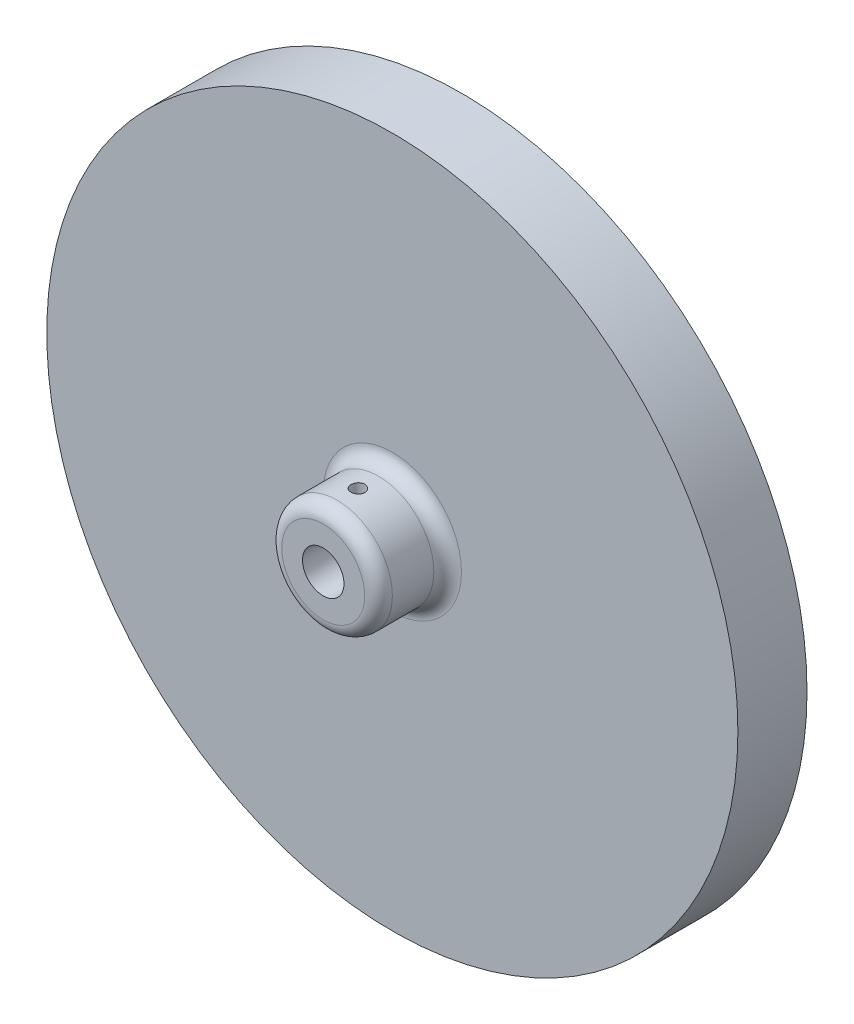
SolidWorks part; units mm, degrees
material "Rubber"
ref_plane "Front Plane" through (0, 0, 0) normal (0, 0, 1) x (1, 0, 0)
ref_plane "Top Plane" through (0, 0, 0) normal (0, 1, 0) x (1, 0, 0)
ref_plane "Right Plane" through (0, 0, 0) normal (1, 0, 0) x (0, 0, -1)
sketch "Sketch1" plane through (0, 0, 0) normal (0, 0, 1) x (1, 0, 0)
  circle A0 centre (0, 0) radius 50
  dimension "D1" = 100
extrude "Boss-Extrude1" add sketch "Sketch1" along normal mid plane 10
sketch "Sketch2" plane through (0, 0, 5) normal (0, 0, 1) x (1, 0, 0)
  circle A0 centre (0, 0) radius 8
  dimension "D1" = 16
extrude "Boss-Extrude2" add sketch "Sketch2" along normal blind 10
sketch "Sketch3" plane through (0, 0, 15) normal (0, 0, 1) x (1, 0, 0)
  circle A0 centre (0, 0) radius 3
  dimension "D1" = 6
extrude "Cut-Extrude1" cut sketch "Sketch3" against normal through all
fillet "Fillet1" radius 2 2 edges at (8, 0, 5) (8, 0, 15)
sketch "Sketch4" plane through (0, 0, 0) normal (0, 1, 0) x (1, 0, 0)
  circle A0 centre (0, -10) radius 1
  dimension "D2" = 2
  dimension "D1" = 10
extrude "Cut-Extrude2" cut sketch "Sketch4" against normal through all both and the other way through all
